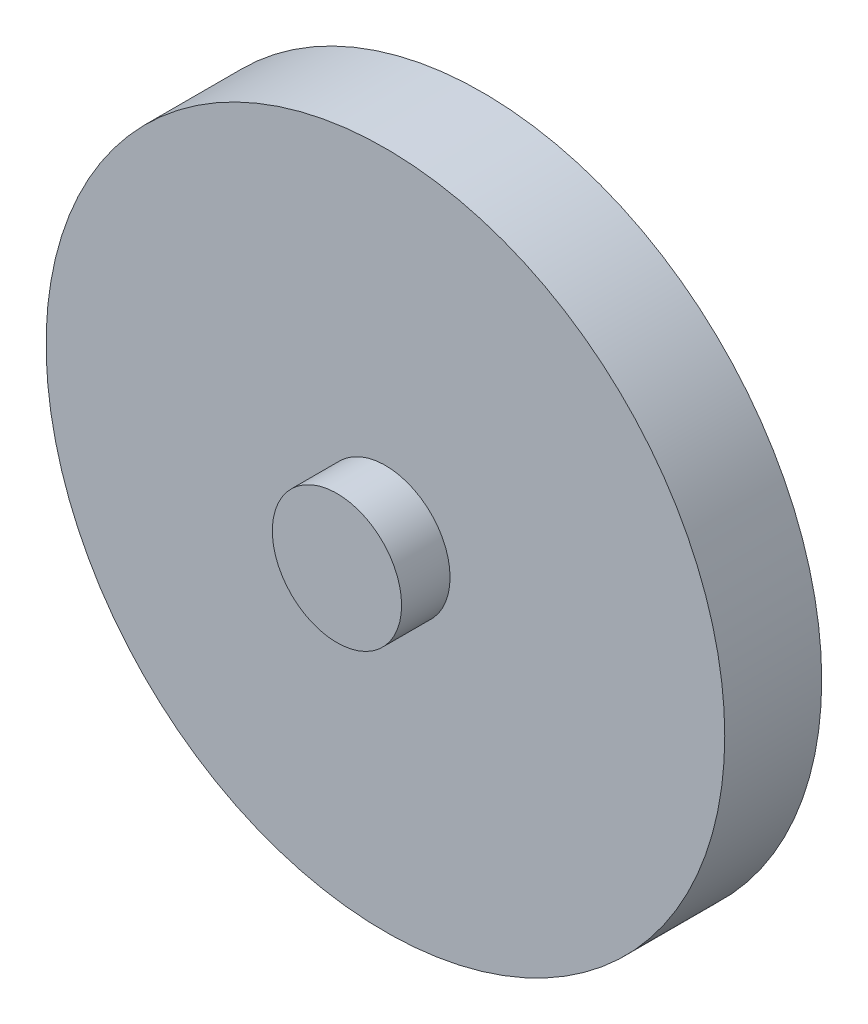
SolidWorks part; units mm, degrees
ref_plane "前视基准面" through (0, 0, 0) normal (0, 0, 1) x (1, 0, 0)
ref_plane "上视基准面" through (0, 0, 0) normal (0, 1, 0) x (1, 0, 0)
ref_plane "右视基准面" through (0, 0, 0) normal (1, 0, 0) x (0, 0, -1)
other "Configuration Table"
sketch "草图1" plane through (0, 0, 0) normal (0, 0, 1) x (1, 0, 0)
  circle A0 centre (0, 0) radius 8
extrude "凸台-拉伸1" add sketch "草图1" along normal blind 6
sketch "草图2" plane through (0, 0, 6) normal (0, 0, 1) x (1, 0, 0)
  circle A0 centre (0, 0) radius 42
extrude "凸台-拉伸2" add sketch "草图2" along normal blind 12
sketch "草图3" plane through (0, 0, 18) normal (0, 0, 1) x (1, 0, 0)
  circle A0 centre (0, 0) radius 8
extrude "凸台-拉伸3" add sketch "草图3" along normal blind 6
sketch "草图4" plane through (0, 0, 18) normal (0, 0, 1) x (1, 0, 0)
  line L0 (37.445, 2.0305) -> (37.5326, 2.0353)
  arc A0 (41.9931, 0.7606) -> (41.5951, 5.8179) centre (0, 0) ccw
  arc A1 (37.5326, 3.8521) -> (37.6744, 2.043) centre (0, 0) cw
